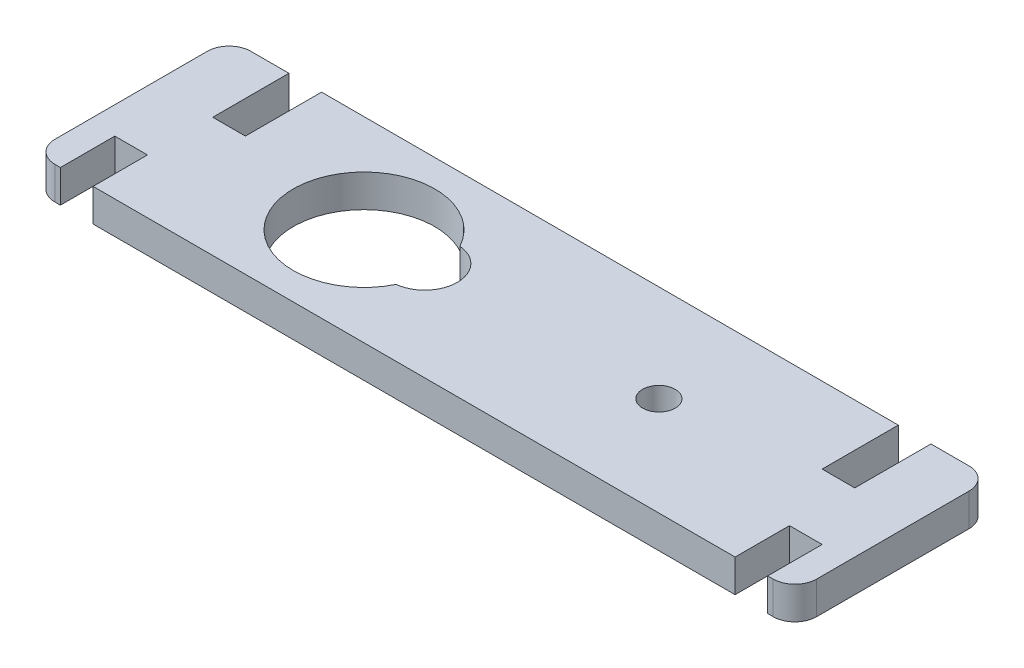
SolidWorks part; units mm, degrees
ref_plane "Front Plane" through (0, 0, 0) normal (0, 0, 1) x (1, 0, 0)
ref_plane "Top Plane" through (0, 0, 0) normal (0, 1, 0) x (1, 0, 0)
ref_plane "Right Plane" through (0, 0, 0) normal (1, 0, 0) x (0, 0, -1)
sketch "Sketch2" plane through (0, 0, 0) normal (0, 1, 0) x (1, 0, 0)
  line L0 (-3.5839, 15.8771) -> (62.4161, 15.8771)
  line L1 (64.4161, 13.8771) -> (64.4161, -0.1229)
  line L2 (62.4161, -2.1229) -> (-3.5839, -2.1229)
  line L3 (-5.5839, -0.1229) -> (-5.5839, 13.8771)
  arc A0 (62.4161, 15.8771) -> (64.4161, 13.8771) centre (62.4161, 13.8771) cw
  arc A1 (64.4161, -0.1229) -> (62.4161, -2.1229) centre (62.4161, -0.1229) cw
  arc A2 (-3.5839, -2.1229) -> (-5.5839, -0.1229) centre (-3.5839, -0.1229) cw
  arc A3 (-5.5839, 13.8771) -> (-3.5839, 15.8771) centre (-3.5839, 13.8771) cw
  dimension "D1" = 2
  dimension "D2" = 2
  dimension "D3" = 2
  dimension "D4" = 2
  dimension "D5" = 70
  dimension "D6" = 18
extrude "Boss-Extrude1" add sketch "Sketch2" along normal blind 3
sketch "Sketch4" plane through (0, 3, 0) normal (0, 1, 0) x (1, 0, 0)
  line L0 (-5.5839, 13.8771) -> (-5.5839, -0.1229) construction
  line L2 (62.4161, 15.8771) -> (-3.5839, 15.8771) construction
  circle A0 centre (15.8161, 6.8771) radius 6.5
  dimension "D3" = 13
  dimension "D1" = 21.4
  dimension "D2" = 9
extrude "Cut-Extrude1" cut sketch "Sketch4" against normal blind 3
sketch "Sketch5" plane through (0, 3, 0) normal (0, 1, 0) x (1, 0, 0)
  line L1 (64.4161, -0.1229) -> (64.4161, 13.8771) construction
  line L2 (62.4161, 15.8771) -> (-3.5839, 15.8771) construction
  circle A0 centre (21.2961, 6.9771) radius 3
  circle A1 centre (42.8161, 6.9771) radius 1.5
  circle A2 centre (15.8161, 6.8771) radius 6.5 construction
  point P4 (0, 0)
  dimension "D1" = 6
  dimension "D2" = 8.9
  dimension "D3" = 3
  dimension "D4" = 21.6
  dimension "D5" = 5.48
extrude "Cut-Extrude2" cut sketch "Sketch5" against normal blind 3
sketch "Sketch6" plane through (0, 3, 0) normal (0, 1, 0) x (1, 0, 0)
  line L0 (62.4161, 15.8771) -> (-3.5839, 15.8771) construction
  line L1 (-0.0839, 15.8771) -> (2.9161, 15.8771)
  line L2 (-0.0839, 15.8771) -> (-0.0839, 8.8771)
  line L3 (-0.0839, 8.8771) -> (2.9161, 8.8771)
  line L4 (2.9161, 15.8771) -> (2.9161, 8.8771)
  line L5 (-5.5839, 13.8771) -> (-5.5839, -0.1229) construction
  line L7 (55.9161, 15.8771) -> (58.9161, 15.8771)
  line L8 (55.9161, 15.8771) -> (55.9161, 8.8771)
  line L9 (55.9161, 8.8771) -> (58.9161, 8.8771)
  line L10 (58.9161, 15.8771) -> (58.9161, 8.8771)
  line L11 (64.4161, -0.1229) -> (64.4161, 13.8771) construction
  dimension "D2" = 3
  dimension "D3" = 5.5
  dimension "D4" = 7
  dimension "D5" = 3
  dimension "D6" = 5.5
extrude "Cut-Extrude3" cut sketch "Sketch6" against normal blind 3
sketch "Sketch7" plane through (0, 3, 0) normal (0, 1, 0) x (1, 0, 0)
  line L6 (-3.5839, -2.1229) -> (62.4161, -2.1229) construction
  line L7 (58.9161, -2.1229) -> (61.9161, -2.1229)
  line L8 (58.9161, -2.1229) -> (58.9161, 2.8771)
  line L9 (58.9161, 2.8771) -> (61.9161, 2.8771)
  line L10 (61.9161, -2.1229) -> (61.9161, 2.8771)
  line L11 (58.9161, 8.8771) -> (58.9161, 15.8771) construction
  line L12 (-0.0839, 15.8771) -> (-0.0839, 8.8771) construction
  line L13 (-0.0839, -2.1229) -> (-3.0839, -2.1229)
  line L14 (-0.0839, -2.1229) -> (-0.0839, 2.8771)
  line L15 (-0.0839, 2.8771) -> (-3.0839, 2.8771)
  line L16 (-3.0839, -2.1229) -> (-3.0839, 2.8771)
  dimension "D1" = 3
  dimension "D2" = 5
  dimension "D3" = 3
  dimension "D4" = 5
extrude "Cut-Extrude4" cut sketch "Sketch7" against normal blind 3
